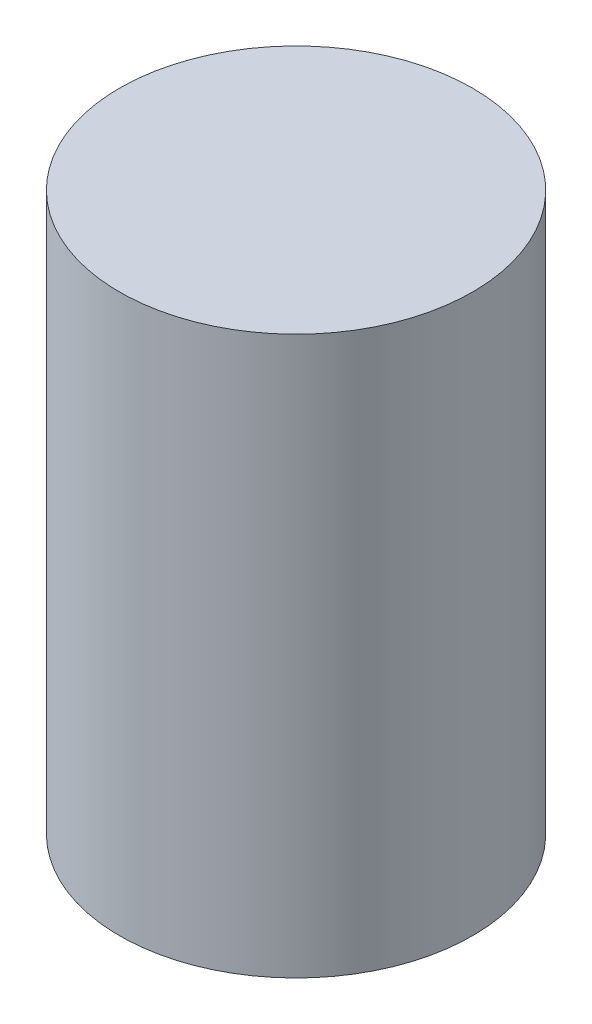
SolidWorks part; units mm, degrees
ref_plane "Front Plane" through (0, 0, 0) normal (0, 0, 1) x (1, 0, 0)
ref_plane "Top Plane" through (0, 0, 0) normal (0, 1, 0) x (1, 0, 0)
ref_plane "Right Plane" through (0, 0, 0) normal (1, 0, 0) x (0, 0, -1)
sketch "Sketch1" plane through (0, 0, 0) normal (0, 1, 0) x (1, 0, 0)
  circle A0 centre (0, 0) radius 4.826
  dimension "D1" = 9.652
extrude "Boss-Extrude1" add sketch "Sketch1" along normal blind 15.24
